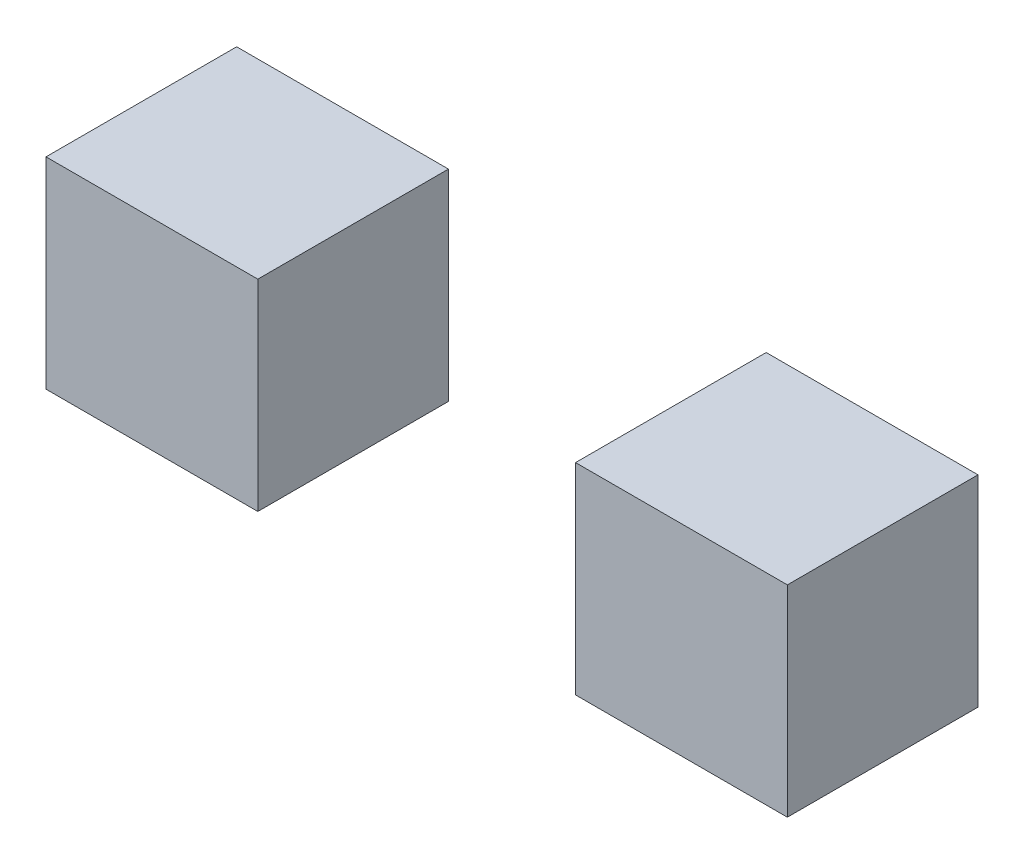
SolidWorks part; units mm, degrees
ref_plane "Front Plane" through (0, 0, 0) normal (0, 0, 1) x (1, 0, 0)
ref_plane "Top Plane" through (0, 0, 0) normal (0, 1, 0) x (1, 0, 0)
ref_plane "Right Plane" through (0, 0, 0) normal (1, 0, 0) x (0, 0, -1)
sketch "Sketch1" plane through (0, 0, 0) normal (0, 0, 1) x (1, 0, 0)
  line L1 (-4.75, -14.75) -> (4.75, -14.75)
  line L2 (-4.75, -14.75) -> (-4.75, -4.75)
  line L3 (-4.75, 14.75) -> (4.75, 14.75)
  line L4 (4.75, -14.75) -> (4.75, -4.75)
  line L5 (-4.75, -14.75) -> (4.75, 14.75) construction
  line L6 (-4.75, 14.75) -> (4.75, -14.75) construction
  line L7 (-14.75, -4.75) -> (-4.75, -4.75)
  line L8 (-14.75, -4.75) -> (-14.75, 4.75)
  line L9 (-14.75, 4.75) -> (-4.75, 4.75)
  line L10 (14.75, -4.75) -> (14.75, 4.75)
  line L11 (-14.75, -4.75) -> (14.75, 4.75) construction
  line L12 (-14.75, 4.75) -> (14.75, -4.75) construction
  line L13 (-4.75, 4.75) -> (-4.75, 14.75)
  line L14 (4.75, 4.75) -> (14.75, 4.75)
  line L15 (4.75, 4.75) -> (4.75, 14.75)
  line L17 (4.75, -4.75) -> (14.75, -4.75)
  point P0 (0, 0)
  point P6 (0, 0)
  dimension "D1" = 10
  dimension "D3" = 10
  dimension "D4" = 9.5
extrude "Boss-Extrude2" add sketch "Sketch1" along normal blind 9
sketch "Sketch2" plane through (0, 0, 9) normal (0, 0, 1) x (1, 0, 0)
  line L6 (-14.75, 4.75) -> (-4.75, -4.75) construction
  line L7 (-9.75, 0) -> (15.25, 0) construction
  line L13 (10.25, -4.75) -> (20.25, -4.75)
  line L14 (10.25, -4.75) -> (10.25, 4.75)
  line L15 (10.25, 4.75) -> (20.25, 4.75)
  line L16 (20.25, -4.75) -> (20.25, 4.75)
  line L17 (10.25, -4.75) -> (20.25, 4.75) construction
  line L18 (10.25, 4.75) -> (20.25, -4.75) construction
  dimension "D1" = 25
  dimension "D2" = 9.5
  dimension "D3" = 10
extrude "Boss-Extrude3" add sketch "Sketch2" against normal blind 9
sketch "Sketch3" plane through (0, 0, 9) normal (0, 0, 1) x (1, 0, 0)
  line L0 (20.25, 4.75) -> (10.25, 4.75) construction
  line L1 (20.25, 4.75) -> (4.75, 4.75) construction
  line L3 (10.25, 22.1157) -> (-4.75, 22.1157)
  line L4 (10.25, 22.1157) -> (10.25, -14.75)
  line L5 (10.25, -14.75) -> (-4.75, -14.75)
  line L6 (-4.75, 22.1157) -> (-4.75, -14.75)
  dimension "D1" = 10
extrude "Cut-Extrude2" cut sketch "Sketch3" against normal blind 9
